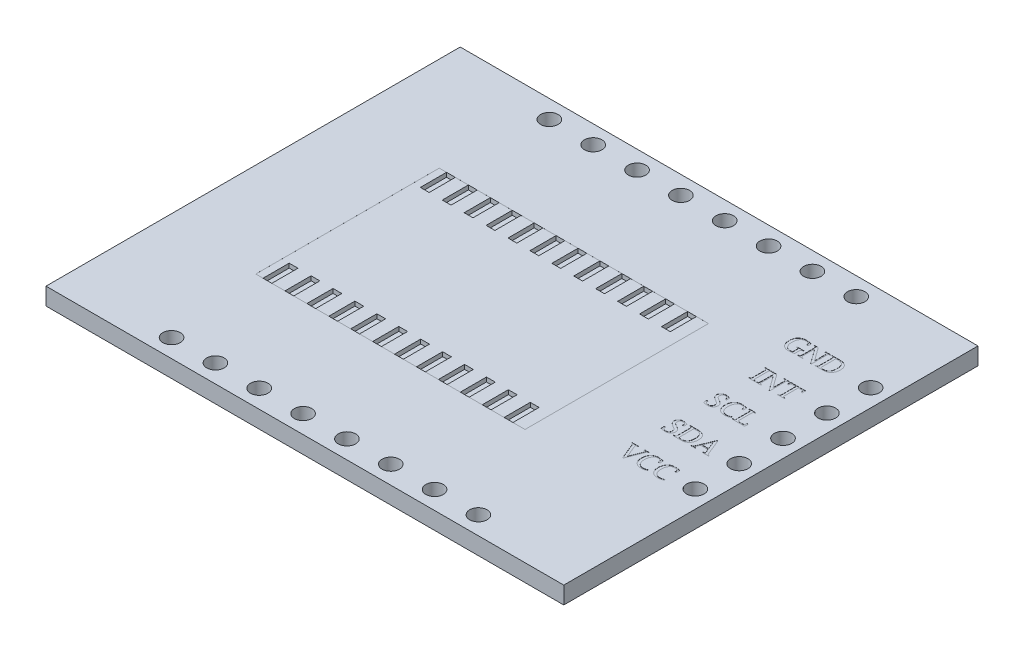
SolidWorks part; units mm, degrees
ref_plane "Front Plane" through (0, 0, 0) normal (0, 0, 1) x (1, 0, 0)
ref_plane "Top Plane" through (0, 0, 0) normal (0, 1, 0) x (1, 0, 0)
ref_plane "Right Plane" through (0, 0, 0) normal (1, 0, 0) x (0, 0, -1)
sketch "Sketch1" plane through (0, 0, 0) normal (0, 1, 0) x (1, 0, 0)
  line L1 (-15, 12) -> (15, 12)
  line L2 (-15, 12) -> (-15, -12)
  line L3 (-15, -12) -> (15, -12)
  line L4 (15, 12) -> (15, -12)
  line L5 (-15, 12) -> (15, -12) construction
  line L6 (-15, -12) -> (15, 12) construction
  point P0 (0, 0)
  dimension "D1" = 30
  dimension "D2" = 24
extrude "Boss-Extrude1" add sketch "Sketch1" along normal blind 1
sketch "Sketch2" plane through (0, 1, 0) normal (0, 1, 0) x (1, 0, 0)
  line L1 (-9.5306, 5.315) -> (6.0694, 5.315)
  line L2 (-9.5306, 5.315) -> (-9.5306, -5.315)
  line L3 (-9.5306, -5.315) -> (6.0694, -5.315)
  line L4 (6.0694, 5.315) -> (6.0694, -5.315)
  line L6 (15, 12) -> (-15, 12) construction
  dimension "D1" = 15.6
  dimension "D2" = 10.63
  dimension "D3" = 6.685
extrude "Cut-Extrude1" cut sketch "Sketch2" against normal blind 0.001
sketch "Sketch3" plane through (0, 0.999, 0) normal (0, 1, 0) x (1, 0, 0)
  line L0 (6.0694, 5.315) -> (-9.5306, 5.315) construction
  line L1 (4.8594, 5.315) -> (5.3694, 5.315)
  line L2 (4.8594, 5.315) -> (4.8594, 3.8)
  line L3 (4.8594, 3.8) -> (5.3694, 3.8)
  line L4 (5.3694, 5.315) -> (5.3694, 3.8)
  line L5 (6.0694, -5.315) -> (6.0694, 5.315) construction
  line L6 (3.5894, 5.315) -> (4.0994, 5.315)
  line L7 (3.5894, 5.315) -> (3.5894, 3.8)
  line L8 (4.0994, 5.315) -> (4.0994, 3.8)
  line L9 (3.5894, 3.8) -> (4.0994, 3.8)
  line L10 (2.3194, 5.315) -> (2.8294, 5.315)
  line L11 (2.3194, 5.315) -> (2.3194, 3.8)
  line L12 (2.8294, 5.315) -> (2.8294, 3.8)
  line L13 (2.3194, 3.8) -> (2.8294, 3.8)
  line L14 (1.0494, 5.315) -> (1.5594, 5.315)
  line L15 (1.0494, 5.315) -> (1.0494, 3.8)
  line L16 (1.5594, 5.315) -> (1.5594, 3.8)
  line L17 (1.0494, 3.8) -> (1.5594, 3.8)
  line L18 (-0.2206, 5.315) -> (0.2894, 5.315)
  line L19 (-0.2206, 5.315) -> (-0.2206, 3.8)
  line L20 (0.2894, 5.315) -> (0.2894, 3.8)
  line L21 (-0.2206, 3.8) -> (0.2894, 3.8)
  line L22 (-1.4906, 5.315) -> (-0.9806, 5.315)
  line L23 (-1.4906, 5.315) -> (-1.4906, 3.8)
  line L24 (-0.9806, 5.315) -> (-0.9806, 3.8)
  line L25 (-1.4906, 3.8) -> (-0.9806, 3.8)
  line L26 (-2.7606, 5.315) -> (-2.2506, 5.315)
  line L27 (-2.7606, 5.315) -> (-2.7606, 3.8)
  line L28 (-2.2506, 5.315) -> (-2.2506, 3.8)
  line L29 (-2.7606, 3.8) -> (-2.2506, 3.8)
  line L30 (-4.0306, 5.315) -> (-3.5206, 5.315)
  line L31 (-4.0306, 5.315) -> (-4.0306, 3.8)
  line L32 (-3.5206, 5.315) -> (-3.5206, 3.8)
  line L33 (-4.0306, 3.8) -> (-3.5206, 3.8)
  line L34 (-5.3006, 5.315) -> (-4.7906, 5.315)
  line L35 (-5.3006, 5.315) -> (-5.3006, 3.8)
  line L36 (-4.7906, 5.315) -> (-4.7906, 3.8)
  line L37 (-5.3006, 3.8) -> (-4.7906, 3.8)
  line L38 (-6.5706, 5.315) -> (-6.0606, 5.315)
  line L39 (-6.5706, 5.315) -> (-6.5706, 3.8)
  line L40 (-6.0606, 5.315) -> (-6.0606, 3.8)
  line L41 (-6.5706, 3.8) -> (-6.0606, 3.8)
  line L42 (-7.8406, 5.315) -> (-7.3306, 5.315)
  line L43 (-7.8406, 5.315) -> (-7.8406, 3.8)
  line L44 (-7.3306, 5.315) -> (-7.3306, 3.8)
  line L45 (-7.8406, 3.8) -> (-7.3306, 3.8)
  line L46 (-9.1106, 5.315) -> (-8.6006, 5.315)
  line L47 (-9.1106, 5.315) -> (-9.1106, 3.8)
  line L48 (-8.6006, 5.315) -> (-8.6006, 3.8)
  line L49 (-9.1106, 3.8) -> (-8.6006, 3.8)
  line L50 (-12.4607, 0) -> (10.3206, 0) construction
  line L51 (-9.5306, -5.315) -> (6.0694, -5.315) construction
  line L52 (4.8594, -3.8) -> (5.3694, -3.8)
  line L53 (4.8594, -5.315) -> (4.8594, -3.8)
  line L54 (5.3694, -5.315) -> (5.3694, -3.8)
  line L55 (4.8594, -5.315) -> (5.3694, -5.315)
  line L56 (3.5894, -5.315) -> (4.0994, -5.315)
  line L57 (4.0994, -5.315) -> (4.0994, -3.8)
  line L58 (3.5894, -5.315) -> (3.5894, -3.8)
  line L59 (3.5894, -3.8) -> (4.0994, -3.8)
  line L60 (2.3194, -3.8) -> (2.8294, -3.8)
  line L61 (2.8294, -5.315) -> (2.8294, -3.8)
  line L62 (2.3194, -5.315) -> (2.8294, -5.315)
  line L63 (2.3194, -5.315) -> (2.3194, -3.8)
  line L64 (1.0494, -3.8) -> (1.5594, -3.8)
  line L65 (1.5594, -5.315) -> (1.5594, -3.8)
  line L66 (1.0494, -5.315) -> (1.5594, -5.315)
  line L67 (1.0494, -5.315) -> (1.0494, -3.8)
  line L68 (-0.2206, -3.8) -> (0.2894, -3.8)
  line L69 (0.2894, -5.315) -> (0.2894, -3.8)
  line L70 (-0.2206, -5.315) -> (-0.2206, -3.8)
  line L71 (-0.2206, -5.315) -> (0.2894, -5.315)
  line L72 (-1.4906, -3.8) -> (-0.9806, -3.8)
  line L73 (-0.9806, -5.315) -> (-0.9806, -3.8)
  line L74 (-1.4906, -5.315) -> (-1.4906, -3.8)
  line L75 (-1.4906, -5.315) -> (-0.9806, -5.315)
  line L76 (-2.2506, -5.315) -> (-2.2506, -3.8)
  line L77 (-2.7606, -5.315) -> (-2.2506, -5.315)
  line L78 (-2.7606, -5.315) -> (-2.7606, -3.8)
  line L79 (-2.7606, -3.8) -> (-2.2506, -3.8)
  line L80 (-4.0306, -3.8) -> (-3.5206, -3.8)
  line L81 (-3.5206, -5.315) -> (-3.5206, -3.8)
  line L82 (-4.0306, -5.315) -> (-4.0306, -3.8)
  line L83 (-4.0306, -5.315) -> (-3.5206, -5.315)
  line L84 (-4.7906, -5.315) -> (-4.7906, -3.8)
  line L85 (-5.3006, -5.315) -> (-4.7906, -5.315)
  line L86 (-5.3006, -5.315) -> (-5.3006, -3.8)
  line L87 (-5.3006, -3.8) -> (-4.7906, -3.8)
  line L88 (-6.5706, -3.8) -> (-6.0606, -3.8)
  line L89 (-6.0606, -5.315) -> (-6.0606, -3.8)
  line L90 (-6.5706, -5.315) -> (-6.5706, -3.8)
  line L91 (-6.5706, -5.315) -> (-6.0606, -5.315)
  line L92 (-7.8406, -3.8) -> (-7.3306, -3.8)
  line L93 (-7.3306, -5.315) -> (-7.3306, -3.8)
  line L94 (-7.8406, -5.315) -> (-7.3306, -5.315)
  line L95 (-7.8406, -5.315) -> (-7.8406, -3.8)
  line L96 (-9.1106, -3.8) -> (-8.6006, -3.8)
  line L97 (-8.6006, -5.315) -> (-8.6006, -3.8)
  line L98 (-9.1106, -5.315) -> (-8.6006, -5.315)
  line L99 (-9.1106, -5.315) -> (-9.1106, -3.8)
  dimension "D1" = 0.51
  dimension "D2" = 1.515
  dimension "D3" = 0.7
  dimension "D5" = 5.315
  dimension "D4" = 12
extrude "Cut-Extrude2" cut sketch "Sketch3" against normal blind 0.25
sketch "Sketch4" plane through (0, 1, 0) normal (0, 1, 0) x (1, 0, 0)
  line L0 (15, -12) -> (15, 12) construction
  line L2 (-16.6658, 0) -> (24.5415, 0) construction
  circle A0 centre (13.99, 6.7929) radius 0.505
  circle A1 centre (13.99, 4.2529) radius 0.505
  circle A2 centre (13.99, 1.7129) radius 0.505
  circle A3 centre (13.99, -0.8271) radius 0.505
  circle A4 centre (13.99, -3.3671) radius 0.505
  circle A5 centre (-8.78, -10.9455) radius 0.505
  circle A6 centre (-6.24, -10.9455) radius 0.505
  circle A7 centre (-3.7, -10.9455) radius 0.505
  circle A8 centre (-1.16, -10.9455) radius 0.505
  circle A9 centre (1.38, -10.9455) radius 0.505
  circle A10 centre (3.92, -10.9455) radius 0.505
  circle A11 centre (6.46, -10.9455) radius 0.505
  circle A12 centre (9, -10.9455) radius 0.505
  circle A13 centre (9, 10.9455) radius 0.505
  circle A14 centre (6.46, 10.9455) radius 0.505
  circle A15 centre (3.92, 10.9455) radius 0.505
  circle A16 centre (1.38, 10.9455) radius 0.505
  circle A17 centre (-1.16, 10.9455) radius 0.505
  circle A18 centre (-3.7, 10.9455) radius 0.505
  circle A19 centre (-6.24, 10.9455) radius 0.505
  circle A20 centre (-8.78, 10.9455) radius 0.505
  dimension "D1" = 1.01
  dimension "D4" = 1.01
  dimension "D6" = 6
  dimension "D2" = 1.01
  dimension "D3" = 5
  dimension "D5" = 8
extrude "Cut-Extrude3" cut sketch "Sketch4" against normal blind 10.25
sketch "Sketch5" plane through (0, 1, 0) normal (0, 1, 0) x (1, 0, 0)
  line L0 (13.99, 6.2879) -> (8.4411, 6.2879) construction
  line L1 (13.99, 3.7479) -> (8.4411, 3.7479) construction
  line L2 (13.99, 1.2079) -> (8.4411, 1.2079) construction
  line L3 (13.99, -1.3321) -> (8.4411, -1.3321) construction
  line L4 (13.99, -3.8721) -> (8.4411, -3.8721) construction
  circle A0 centre (13.99, 6.7929) radius 0.505 construction
  text T0 "GND    " font "Lucida Bright" height 1
  text T1 "INT    " font "Lucida Bright" height 1
  text T2 "SCL    " font "Lucida Bright" height 1
  text T3 "SDA   " font "Lucida Bright" height 1
  text T4 "VCC   " font "Lucida Bright" height 1
  dimension "D1" = 5
extrude "Cut-Extrude4" cut sketch "Sketch5" against normal blind 0.01
